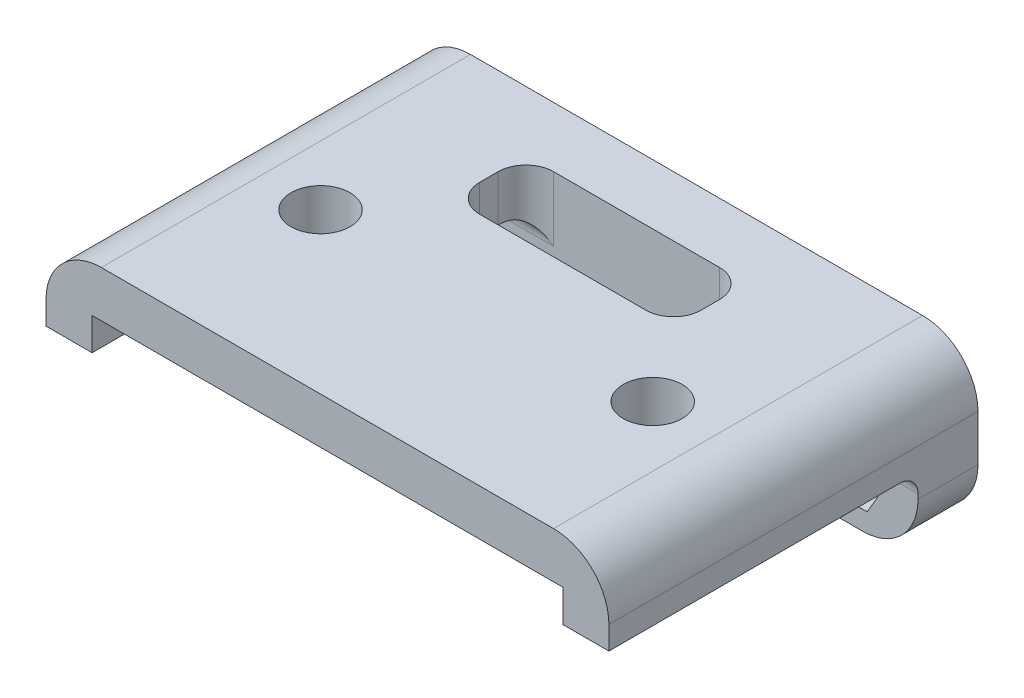
SolidWorks part; units mm, degrees
ref_plane "Front Plane" through (0, 0, 0) normal (0, 0, 1) x (1, 0, 0)
ref_plane "Top Plane" through (0, 0, 0) normal (0, 1, 0) x (1, 0, 0)
ref_plane "Right Plane" through (0, 0, 0) normal (1, 0, 0) x (0, 0, -1)
sketch "Sketch1" plane through (0, 0, 0) normal (0, 0, 1) x (1, 0, 0)
  line L0 (-15.25, 4.25) -> (15.25, 4.25)
  line L1 (-15.25, 4.25) -> (-15.25, -4.25)
  line L2 (-15.25, -4.25) -> (15.25, -4.25)
  line L3 (15.25, -4.25) -> (15.25, 4.25)
  point P0 (-15.25, 0)
  point P3 (0, 4.25)
  dimension "D1" = 30.5
  dimension "D2" = 8.5
extrude "Boss-Extrude1" add sketch "Sketch1" along normal blind 20
shell "Shell1" thickness 2.5
sketch "Sketch2" plane through (0, -4.25, 0) normal (0, -1, 0) x (1, 0, 0)
  line L0 (-6, 20) -> (6, 20)
  line L1 (-15.25, 20) -> (15.25, 20) construction
  line L2 (6, 20) -> (6, 4)
  line L3 (0, 20) -> (0, 11.1176) construction
  line L4 (-6, 20) -> (-6, 4)
  line L5 (-6, 4) -> (6, 4)
  dimension "D1" = 6
  dimension "D2" = 16
extrude "Cut-Extrude2" cut sketch "Sketch2" against normal blind 3
sketch "Sketch3" plane through (0, 4.25, 0) normal (0, 1, 0) x (1, 0, 0)
  line L0 (-6, -3.25) -> (-6, -7.25)
  line L1 (-6, -20) -> (-6, -4) construction
  line L2 (-6, -7.25) -> (6, -7.25)
  line L3 (6, -4) -> (6, -20) construction
  line L4 (6, -7.25) -> (6, -3.25)
  line L5 (6, -3.25) -> (-6, -3.25)
  dimension "D1" = 4
extrude "Cut-Extrude3" cut sketch "Sketch3" against normal blind 4
sketch "Sketch4" plane through (0, 4.25, 0) normal (0, 1, 0) x (1, 0, 0)
  circle A0 centre (8.9747, -11.35) radius 1.6 construction
  circle A1 centre (-9.0253, -11.35) radius 1.6 construction
  circle A2 centre (8.9747, -11.35) radius 1.6
  circle A3 centre (-9.0253, -11.35) radius 1.6
extrude "Cut-Extrude4" cut sketch "Sketch4" against normal blind 10
fillet "Fillet1" radius 3 1 edges at (15.25, 4.25, 10)
fillet "Fillet2" radius 3 1 edges at (-15.25, 4.25, 10)
fillet "Fillet3" radius 3 1 edges at (15.25, -4.25, 10)
fillet "Fillet4" radius 3 1 edges at (-15.25, -4.25, 10)
sketch "Sketch5" plane through (0, 0, 0) normal (0, 0, -1) x (-1, 0, 0)
  line L0 (-15.25, -1.25) -> (-15.25, 1.25) construction
  line L1 (0, 4.25) -> (0, -4.25) construction
  line L2 (-12.25, 4.25) -> (12.25, 4.25) construction
  line L3 (12.25, -4.25) -> (-12.25, -4.25) construction
  circle A0 centre (-10.75, -0.1829) radius 1.45
  circle A1 centre (10.75, -0.1829) radius 1.45
  dimension "D2" = 2.9
  dimension "D1" = 4.5
extrude "Cut-Extrude5" cut sketch "Sketch5" against normal blind 29
sketch "Sketch10" plane through (0, 0, 0) normal (0, 0, -1) x (-1, 0, 0)
  line L0 (0, 4.25) -> (0, -9.2586) construction
  line L1 (-12.25, 4.25) -> (12.25, 4.25) construction
sketch "Sketch12" plane through (0, 0, 2.5) normal (0, 0, 1) x (1, 0, 0)
  line L1 (-12.75, 1.75) -> (12.75, 1.75)
  line L2 (-12.75, 1.75) -> (-12.75, -1.75)
  line L3 (-12.75, -1.75) -> (12.75, -1.75)
  line L4 (12.75, 1.75) -> (12.75, -1.75)
extrude "Boss-Extrude3" add sketch "Sketch12" along normal up to vertex
sketch "Sketch13" plane through (0, 0, 4) normal (0, 0, 1) x (1, 0, 0)
  circle A0 centre (-10.75, -0.1829) radius 1.462
  circle A1 centre (10.75, -0.1829) radius 1.4591
extrude "Cut-Extrude6" cut sketch "Sketch13" against normal blind 2
sketch "Sketch14" plane through (0, 0, 4) normal (0, 0, 1) x (1, 0, 0)
  line L1 (-7.25, -0.1829) -> (-9, 2.8482)
  line L2 (-9, 2.8482) -> (-12.5, 2.8482)
  line L3 (-12.5, 2.8482) -> (-14.25, -0.1829)
  line L4 (-14.25, -0.1829) -> (-12.5, -3.214)
  line L5 (-12.5, -3.214) -> (-9, -3.214)
  line L6 (-9, -3.214) -> (-7.25, -0.1829)
  line L7 (14.25, -0.1829) -> (12.5, 2.8482)
  line L8 (12.5, 2.8482) -> (9, 2.8482)
  line L9 (9, 2.8482) -> (7.25, -0.1829)
  line L10 (7.25, -0.1829) -> (9, -3.214)
  line L11 (9, -3.214) -> (12.5, -3.214)
  line L12 (12.5, -3.214) -> (14.25, -0.1829)
  circle A0 centre (-10.75, -0.1829) radius 3.0311 construction
  circle A1 centre (10.75, -0.1829) radius 3.0311 construction
  dimension "D1" = 3.5
  dimension "D2" = 3.5
extrude "Cut-Extrude7" cut sketch "Sketch14" along normal blind 5 from offset 2 offset against normal yes
fillet "Fillet5" radius 1.5 1 edges at (6, 3, 7.25)
fillet "Fillet6" radius 1.5 1 edges at (-6, 3, 7.25)
fillet "Fillet7" radius 1.5 1 edges at (-6, 3, 3.25)
fillet "Fillet8" radius 1.5 1 edges at (6, 3, 3.25)
fillet "Fillet9" radius 1 1 edges at (6, -3, 4)
fillet "Fillet10" radius 1 1 edges at (-6, -3, 4)
sketch "Sketch15" plane through (0, 0, 20) normal (0, 0, 1) x (1, 0, 0)
  line L0 (-15.25, 0) -> (15.25, 0)
  line L1 (-15.25, 1.25) -> (-15.25, -1.25) construction
  line L2 (15.25, -1.25) -> (15.25, 1.25) construction
  line L3 (15.25, 0) -> (15.25, -4.25)
  line L4 (15.25, -4.25) -> (-15.25, -4.25)
  line L5 (-15.25, -4.25) -> (-15.25, 0)
extrude "Cut-Extrude8" cut sketch "Sketch15" against normal up to surface (16.75 mm away) up to face at (0, 1.1634, 3.25)
fillet "Fillet13" radius 1 1 edges at (14.6972, 0, 3.25)
fillet "Fillet14" radius 1 1 edges at (-14.6972, 0, 3.25)
fillet "Fillet15" radius 1 2 edges at (6.433, 1.75, 3.25) (-6.433, 1.75, 3.25)
sketch "Sketch16" plane through (0, 0, 0) normal (0, -1, 0) x (1, 0, 0)
  line L0 (-10.0612, 15.2135) -> (-10.0612, 7.4865)
  line L1 (10.0106, 15.2135) -> (10.0106, 7.4865)
  arc A0 (10.0106, 7.4865) -> (10.0106, 15.2135) centre (8.9747, 11.35) ccw construction
  arc A1 (-10.0612, 15.2135) -> (-10.0612, 7.4865) centre (-9.0253, 11.35) ccw construction
  arc A2 (10.0106, 7.4865) -> (10.0106, 15.2135) centre (8.9747, 11.35) ccw
  arc A3 (-10.0612, 15.2135) -> (-10.0612, 7.4865) centre (-9.0253, 11.35) ccw
extrude "Cut-Extrude9" cut sketch "Sketch16" against normal up to surface (1.75 mm away) up to face at (8.9747, 1.75, 9.75)
